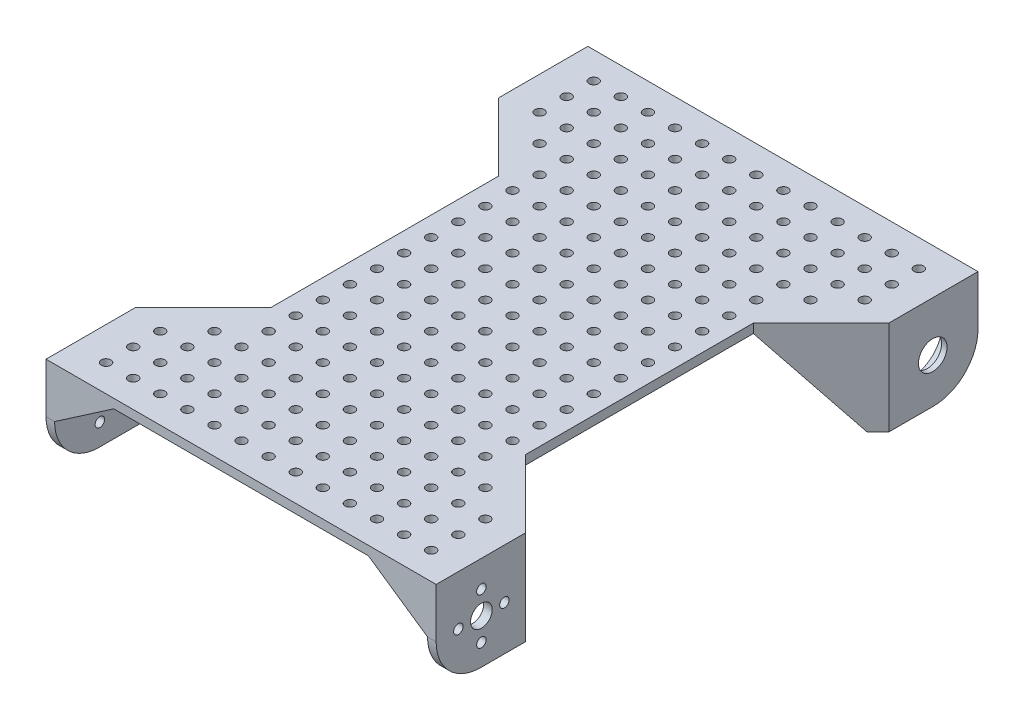
SolidWorks part; units mm, degrees
ref_plane "Alzado" through (0, 0, 0) normal (0, 0, 1) x (1, 0, 0)
ref_plane "Planta" through (0, 0, 0) normal (0, 1, 0) x (1, 0, 0)
ref_plane "Vista lateral" through (0, 0, 0) normal (1, 0, 0) x (0, 0, -1)
sketch "Croquis1" plane through (0, 0, 0) normal (1, 0, 0) x (0, 0, -1)
  point P0 (0, 0)
  line B0 (-67.1, 0) -> (67.1, 0)
  line B1 (-100, 0) -> (-100, 3.3682)
  line B2 (-100, 3.3682) -> (100, 3.3682)
  line B3 (-100, 0) -> (-100, -15)
  line B4 (-67.1, -15) -> (-70.1, -15) construction
  line B5 (-100, 0) -> (-67.1, 0) construction
  line B6 (-67.1, -15) -> (-67.1, 0)
  line B7 (0, 3.3682) -> (0, 0) construction
  line B8 (100, 0) -> (67.1, 0) construction
  line B9 (100, 0) -> (100, 3.3682)
  line B10 (100, 0) -> (67.1, 0) construction
  line B11 (100, 0) -> (100, -15)
  line B12 (67.1, -15) -> (67.1, 0)
  arc B13 (-100, -15) -> (-67.1, -15) centre (-83.55, -15) ccw
  circle B14 centre (-83.3, -15) radius 13.2 construction
  circle B15 centre (-83.3, -23.5) radius 1.75
  circle B16 centre (-91.8, -15) radius 1.75
  circle B17 centre (-74.8, -15) radius 1.75
  circle B18 centre (-83.3, -6.5) radius 1.75
  circle B19 centre (-83.3, -15) radius 4
  circle B20 centre (83.3, -15) radius 5.275
  arc B21 (100, -15) -> (67.1, -15) centre (83.55, -15) cw
sketch_block_instance "Bloque1-1"
sketch_block "Bloque1"
extrude "Saliente-Extruir1" add sketch "Croquis1" along normal blind 2
sketch "Croquis2" plane through (2, 0, 0) normal (1, 0, 0) x (0, 0, -1)
  line L0 (100, -15) -> (100, 3.3682) construction
  line L1 (-100, 3.3682) -> (100, 3.3682)
  line L2 (-100, 3.3682) -> (-100, 0)
  line L3 (-100, 0) -> (100, 0)
  line L4 (100, 3.3682) -> (100, 0)
extrude "Saliente-Extruir2" add sketch "Croquis2" along normal blind 70
sketch "Croquis3" plane through (0, 0, 0) normal (0, -1, 0) x (1, 0, 0)
  line L0 (0, 67.1) -> (25, 42.1)
  line L1 (25, 42.1) -> (25, -42.1)
  line L2 (25, -42.1) -> (0, -67.1)
  line L3 (0, -67.1) -> (0, 67.1)
  dimension "D1" = 25
  dimension "D2" = 25
  dimension "D3" = 25
extrude "Cortar-Extruir1" cut sketch "Croquis3" against normal through all
sketch "Croquis5" plane through (2, 0, 0) normal (1, 0, 0) x (0, 0, -1)
  line L3 (-67.1, 0) -> (-100, 0)
  line L4 (-100, 0) -> (-100, -15)
  line L5 (-67.1, -15) -> (-67.1, 0)
  line L6 (-67.1, 0) -> (-100, 0)
  line L7 (-100, 0) -> (-100, -15)
  line L8 (-67.1, -15) -> (-67.1, 0)
  circle A1 centre (-83.3, -23.5) radius 1.75
  circle A2 centre (-83.3, -23.5) radius 1.75
  circle A3 centre (-91.8, -15) radius 1.75
  circle A4 centre (-91.8, -15) radius 1.75
  circle A5 centre (-74.8, -15) radius 1.75
  circle A6 centre (-74.8, -15) radius 1.75
  circle A7 centre (-83.3, -6.5) radius 1.75
  circle A8 centre (-83.3, -6.5) radius 1.75
  circle A9 centre (-83.3, -15) radius 4
  circle A10 centre (-83.3, -15) radius 4
  arc A11 (-100, -15) -> (-67.1, -15) centre (-83.55, -15) ccw
  arc A12 (-100, -15) -> (-67.1, -15) centre (-83.55, -15) ccw
  dimension "D1" = 0
  dimension "D2" = 0
  dimension "D3" = 0
  dimension "D4" = 0
  dimension "D5" = 0
  dimension "D6" = 0
extrude "Saliente-Extruir3" add sketch "Croquis5" along normal blind 1.175
sketch "Croquis6" plane through (2, 0, 0) normal (1, 0, 0) x (0, 0, -1)
  line L3 (100, 0) -> (67.1, 0)
  line L4 (67.1, 0) -> (67.1, -15)
  line L5 (100, -15) -> (100, 0)
  line L6 (100, 0) -> (67.1, 0)
  line L7 (67.1, 0) -> (67.1, -15)
  line L8 (100, -15) -> (100, 0)
  circle A0 centre (83.55, -15) radius 11.25
  arc A1 (67.1, -15) -> (100, -15) centre (83.55, -15) ccw
  arc A2 (67.1, -15) -> (100, -15) centre (83.55, -15) ccw
  dimension "D2" = 22.5
  dimension "D1" = 0
extrude "Saliente-Extruir4" add sketch "Croquis6" along normal blind 6.05
sketch "Croquis8" plane through (3.175, 0, 0) normal (1, 0, 0) x (0, 0, -1)
  line L0 (-83.55, -31.45) -> (-67.1, -31.45)
  line L1 (-67.1, -31.45) -> (-67.1, -15)
  line L2 (83.55, -31.45) -> (67.1, -31.45)
  line L3 (-67.1, -15) -> (-67.1, 0)
  line L4 (-67.1, 0) -> (-100, 0)
  line L5 (-100, 0) -> (-100, -15)
  line L9 (67.1, -31.45) -> (67.1, -15)
  arc A0 (67.1, -15) -> (100, -15) centre (83.55, -15) ccw construction
  arc A1 (-100, -15) -> (-67.1, -15) centre (-83.55, -15) ccw
  arc A2 (-83.55, -31.45) -> (-67.1, -15) centre (-83.55, -15) ccw
  arc A3 (67.1, -15) -> (83.55, -31.45) centre (83.55, -15) ccw
  dimension "D1" = 0
extrude "Saliente-Extruir5" add sketch "Croquis8" against normal up to surface (3.175 mm away) up to face at (0, -15, 79.3)
sketch "Croquis10" plane through (3.175, 0, 0) normal (1, 0, 0) x (0, 0, -1)
  line L2 (67.1, -15) -> (67.1, -31.45)
  line L3 (67.1, -31.45) -> (83.55, -31.45)
  line L4 (67.1, -15) -> (67.1, -31.45)
  line L5 (67.1, -31.45) -> (83.55, -31.45)
  arc A1 (67.1, -15) -> (83.55, -31.45) centre (83.55, -15) ccw
  arc A2 (67.1, -15) -> (83.55, -31.45) centre (83.55, -15) ccw
  dimension "D1" = 0
extrude "Saliente-Extruir6" add sketch "Croquis10" along normal up to surface (4.875 mm away) up to face at (8.05, -11.6125, -83.55)
sketch "Croquis9" plane through (0, 0, 0) normal (0, -1, 0) x (1, 0, 0)
  line L0 (0, 67.1) -> (25, 42.1)
  line L1 (25, 42.1) -> (25, 45.275)
  line L2 (25, 45.275) -> (3.175, 67.1)
  line L3 (0, -67.1) -> (25, -42.1)
  line L4 (25, -42.1) -> (25, -50.15)
  line L5 (25, -50.15) -> (8.05, -67.1)
  line L6 (8.05, -100) -> (8.05, -67.1) construction
  line L7 (8.05, -67.1) -> (0, -67.1)
  line M3 (0, -67.1) -> (8.05, -67.1)
  line M9 (3.175, 67.1) -> (0, 67.1)
  line M10 (0, 67.1) -> (25, 42.1)
  line M12 (25, -42.1) -> (0, -67.1)
extrude "Saliente-Extruir7" add sketch "Croquis9" along normal up to surface (31.45 mm away) contours L1 L2 M9 M10 | L5 L4 M12 M3 up to face at (1.5875, -31.45, 75.325)
sketch "Croquis11" plane through (37.575, 0, -37.575) normal (0.7071, 0, -0.7071) x (-0.7071, 0, -0.7071)
  line L0 (41.7547, -31.45) -> (12.0915, 0)
  line L1 (12.0915, 0) -> (12.0915, -31.45)
  line L2 (12.0915, -31.45) -> (41.7547, -31.45)
extrude "Cortar-Extruir2" cut sketch "Croquis11" against normal through all
sketch "Croquis12" plane through (35.1375, 0, 35.1375) normal (0.7071, 0, 0.7071) x (0.7071, 0, -0.7071)
  line L0 (-45.2018, -31.45) -> (-12.0915, 0)
  line L1 (-12.0915, 0) -> (-12.0915, -31.45)
  line L2 (-12.0915, -31.45) -> (-45.2018, -31.45)
extrude "Cortar-Extruir3" cut sketch "Croquis12" against normal through all
sketch "Croquis13" plane through (3.175, 0, 0) normal (1, 0, 0) x (0, 0, -1)
  line L0 (-100, 0) -> (-100, -15) construction
  line L1 (-100, 0) -> (-97, 0)
  line L2 (-100, 0) -> (-100, -15)
  line L3 (-100, -15) -> (-97, -15)
  line L4 (-97, 0) -> (-97, -15)
  line L5 (100, 0) -> (97, 0)
  line L6 (100, 0) -> (100, -15)
  line L7 (100, -15) -> (97, -15)
  line L8 (97, 0) -> (97, -15)
  line L9 (100, -15) -> (100, 0) construction
  point P10 (-100, -11.6728)
  point P14 (100, -13.4156)
  dimension "D1" = 3
  dimension "D2" = 3
extrude "Saliente-Extruir8" add sketch "Croquis13" along normal up to surface (21.825 mm away) up to face at (25, 1.6841, 0)
sketch "Croquis14" plane through (0, 0, 100) normal (0, 0, 1) x (1, 0, 0)
  line L0 (3.175, -15) -> (25, 0)
  line L1 (25, 0) -> (25, -15)
  line L2 (25, -15) -> (3.175, -15)
extrude "Cortar-Extruir4" cut sketch "Croquis14" against normal up to surface (3 mm away) up to face at (14.0875, -7.5, 97)
sketch "Croquis15" plane through (0, 0, -100) normal (0, 0, -1) x (-1, 0, 0)
  line L0 (-8.05, -15) -> (-25, 0)
  line L1 (-25, 0) -> (-25, -15)
  line L2 (-25, -15) -> (-8.05, -15)
extrude "Cortar-Extruir5" cut sketch "Croquis15" against normal up to surface (3 mm away) up to face at (16.525, -7.5, -97)
ref_plane "Plano1" through (72, 0, 0) normal (1, 0, 0) x (0, 0, -1)
mirror "Simetría1" about plane through (72, 0, 0) normal (1, 0, 0) of bodies 113
sketch "Croquis16" plane through (0, 0, 0) normal (0, -1, 0) x (1, 0, 0)
  line L0 (3.175, 97) -> (3.175, -97) construction
  line L1 (25, -97) -> (8.05, -97) construction
  line L2 (119, 100) -> (25, 100) construction
  line L3 (72, 100) -> (72, -100) construction
  line L4 (119, 100) -> (25, 100) construction
  line L5 (119, -100) -> (25, -100) construction
  circle A0 centre (12.175, 90) radius 1.75
  circle A1 centre (22.175, 90) radius 1.75
  circle A2 centre (32.175, 90) radius 1.75
  circle A3 centre (42.175, 90) radius 1.75
  circle A4 centre (52.175, 90) radius 1.75
  circle A5 centre (62.175, 90) radius 1.75
  circle A6 centre (72.175, 90) radius 1.75
  circle A7 centre (82.175, 90) radius 1.75
  circle A8 centre (92.175, 90) radius 1.75
  circle A9 centre (102.175, 90) radius 1.75
  circle A10 centre (112.175, 90) radius 1.75
  circle A11 centre (122.175, 90) radius 1.75
  circle A12 centre (132.175, 90) radius 1.75
  circle A13 centre (22.175, 80) radius 1.75
  circle A14 centre (32.175, 80) radius 1.75
  circle A15 centre (42.175, 80) radius 1.75
  circle A16 centre (52.175, 80) radius 1.75
  circle A17 centre (62.175, 80) radius 1.75
  circle A18 centre (72.175, 80) radius 1.75
  circle A19 centre (82.175, 80) radius 1.75
  circle A20 centre (92.175, 80) radius 1.75
  circle A21 centre (102.175, 80) radius 1.75
  circle A22 centre (112.175, 80) radius 1.75
  circle A23 centre (122.175, 80) radius 1.75
  circle A24 centre (132.175, 80) radius 1.75
  circle A25 centre (22.175, 70) radius 1.75
  circle A26 centre (32.175, 70) radius 1.75
  circle A27 centre (42.175, 70) radius 1.75
  circle A28 centre (52.175, 70) radius 1.75
  circle A29 centre (62.175, 70) radius 1.75
  circle A30 centre (72.175, 70) radius 1.75
  circle A31 centre (82.175, 70) radius 1.75
  circle A32 centre (92.175, 70) radius 1.75
  circle A33 centre (102.175, 70) radius 1.75
  circle A34 centre (112.175, 70) radius 1.75
  circle A35 centre (122.175, 70) radius 1.75
  circle A36 centre (132.175, 70) radius 1.75
  circle A37 centre (22.175, 60) radius 1.75
  circle A38 centre (32.175, 60) radius 1.75
  circle A39 centre (42.175, 60) radius 1.75
  circle A40 centre (52.175, 60) radius 1.75
  circle A41 centre (62.175, 60) radius 1.75
  circle A42 centre (72.175, 60) radius 1.75
  circle A43 centre (82.175, 60) radius 1.75
  circle A44 centre (92.175, 60) radius 1.75
  circle A45 centre (102.175, 60) radius 1.75
  circle A46 centre (112.175, 60) radius 1.75
  circle A47 centre (122.175, 60) radius 1.75
  circle A50 centre (32.175, 50) radius 1.75
  circle A51 centre (42.175, 50) radius 1.75
  circle A52 centre (52.175, 50) radius 1.75
  circle A53 centre (62.175, 50) radius 1.75
  circle A54 centre (72.175, 50) radius 1.75
  circle A55 centre (82.175, 50) radius 1.75
  circle A56 centre (92.175, 50) radius 1.75
  circle A57 centre (102.175, 50) radius 1.75
  circle A58 centre (112.175, 50) radius 1.75
  circle A62 centre (32.175, 40) radius 1.75
  circle A63 centre (42.175, 40) radius 1.75
  circle A64 centre (52.175, 40) radius 1.75
  circle A65 centre (62.175, 40) radius 1.75
  circle A66 centre (72.175, 40) radius 1.75
  circle A67 centre (82.175, 40) radius 1.75
  circle A68 centre (92.175, 40) radius 1.75
  circle A69 centre (102.175, 40) radius 1.75
  circle A70 centre (112.175, 40) radius 1.75
  circle A74 centre (32.175, 30) radius 1.75
  circle A75 centre (42.175, 30) radius 1.75
  circle A76 centre (52.175, 30) radius 1.75
  circle A77 centre (62.175, 30) radius 1.75
  circle A78 centre (72.175, 30) radius 1.75
  circle A79 centre (82.175, 30) radius 1.75
  circle A80 centre (92.175, 30) radius 1.75
  circle A81 centre (102.175, 30) radius 1.75
  circle A82 centre (112.175, 30) radius 1.75
  circle A86 centre (32.175, 20) radius 1.75
  circle A87 centre (42.175, 20) radius 1.75
  circle A88 centre (52.175, 20) radius 1.75
  circle A89 centre (62.175, 20) radius 1.75
  circle A90 centre (72.175, 20) radius 1.75
  circle A91 centre (82.175, 20) radius 1.75
  circle A92 centre (92.175, 20) radius 1.75
  circle A93 centre (102.175, 20) radius 1.75
  circle A94 centre (112.175, 20) radius 1.75
  circle A98 centre (32.175, 10) radius 1.75
  circle A99 centre (42.175, 10) radius 1.75
  circle A100 centre (52.175, 10) radius 1.75
  circle A101 centre (62.175, 10) radius 1.75
  circle A102 centre (72.175, 10) radius 1.75
  circle A103 centre (82.175, 10) radius 1.75
  circle A104 centre (92.175, 10) radius 1.75
  circle A105 centre (102.175, 10) radius 1.75
  circle A106 centre (112.175, 10) radius 1.75
  circle A110 centre (32.175, 0) radius 1.75
  circle A111 centre (42.175, 0) radius 1.75
  circle A112 centre (52.175, 0) radius 1.75
  circle A113 centre (62.175, 0) radius 1.75
  circle A114 centre (72.175, 0) radius 1.75
  circle A115 centre (82.175, 0) radius 1.75
  circle A116 centre (92.175, 0) radius 1.75
  circle A117 centre (102.175, 0) radius 1.75
  circle A118 centre (112.175, 0) radius 1.75
  circle A122 centre (32.175, -10) radius 1.75
  circle A123 centre (42.175, -10) radius 1.75
  circle A124 centre (52.175, -10) radius 1.75
  circle A125 centre (62.175, -10) radius 1.75
  circle A126 centre (72.175, -10) radius 1.75
  circle A127 centre (82.175, -10) radius 1.75
  circle A128 centre (92.175, -10) radius 1.75
  circle A129 centre (102.175, -10) radius 1.75
  circle A130 centre (112.175, -10) radius 1.75
  circle A134 centre (32.175, -20) radius 1.75
  circle A135 centre (42.175, -20) radius 1.75
  circle A136 centre (52.175, -20) radius 1.75
  circle A137 centre (62.175, -20) radius 1.75
  circle A138 centre (72.175, -20) radius 1.75
  circle A139 centre (82.175, -20) radius 1.75
  circle A140 centre (92.175, -20) radius 1.75
  circle A141 centre (102.175, -20) radius 1.75
  circle A142 centre (112.175, -20) radius 1.75
  circle A146 centre (32.175, -30) radius 1.75
  circle A147 centre (42.175, -30) radius 1.75
  circle A148 centre (52.175, -30) radius 1.75
  circle A149 centre (62.175, -30) radius 1.75
  circle A150 centre (72.175, -30) radius 1.75
  circle A151 centre (82.175, -30) radius 1.75
  circle A152 centre (92.175, -30) radius 1.75
  circle A153 centre (102.175, -30) radius 1.75
  circle A154 centre (112.175, -30) radius 1.75
  circle A158 centre (32.175, -40) radius 1.75
  circle A159 centre (42.175, -40) radius 1.75
  circle A160 centre (52.175, -40) radius 1.75
  circle A161 centre (62.175, -40) radius 1.75
  circle A162 centre (72.175, -40) radius 1.75
  circle A163 centre (82.175, -40) radius 1.75
  circle A164 centre (92.175, -40) radius 1.75
  circle A165 centre (102.175, -40) radius 1.75
  circle A166 centre (112.175, -40) radius 1.75
  circle A170 centre (32.175, -50) radius 1.75
  circle A171 centre (42.175, -50) radius 1.75
  circle A172 centre (52.175, -50) radius 1.75
  circle A173 centre (62.175, -50) radius 1.75
  circle A174 centre (72.175, -50) radius 1.75
  circle A175 centre (82.175, -50) radius 1.75
  circle A176 centre (92.175, -50) radius 1.75
  circle A177 centre (102.175, -50) radius 1.75
  circle A178 centre (112.175, -50) radius 1.75
  circle A181 centre (22.175, -60) radius 1.75
  circle A182 centre (32.175, -60) radius 1.75
  circle A183 centre (42.175, -60) radius 1.75
  circle A184 centre (52.175, -60) radius 1.75
  circle A185 centre (62.175, -60) radius 1.75
  circle A186 centre (72.175, -60) radius 1.75
  circle A187 centre (82.175, -60) radius 1.75
  circle A188 centre (92.175, -60) radius 1.75
  circle A189 centre (102.175, -60) radius 1.75
  circle A190 centre (112.175, -60) radius 1.75
  circle A191 centre (122.175, -60) radius 1.75
  circle A193 centre (22.175, -70) radius 1.75
  circle A194 centre (32.175, -70) radius 1.75
  circle A195 centre (42.175, -70) radius 1.75
  circle A196 centre (52.175, -70) radius 1.75
  circle A197 centre (62.175, -70) radius 1.75
  circle A198 centre (72.175, -70) radius 1.75
  circle A199 centre (82.175, -70) radius 1.75
  circle A200 centre (92.175, -70) radius 1.75
  circle A201 centre (102.175, -70) radius 1.75
  circle A202 centre (112.175, -70) radius 1.75
  circle A203 centre (122.175, -70) radius 1.75
  circle A204 centre (132.175, -70) radius 1.75
  circle A205 centre (22.175, -80) radius 1.75
  circle A206 centre (32.175, -80) radius 1.75
  circle A207 centre (42.175, -80) radius 1.75
  circle A208 centre (52.175, -80) radius 1.75
  circle A209 centre (62.175, -80) radius 1.75
  circle A210 centre (72.175, -80) radius 1.75
  circle A211 centre (82.175, -80) radius 1.75
  circle A212 centre (92.175, -80) radius 1.75
  circle A213 centre (102.175, -80) radius 1.75
  circle A214 centre (112.175, -80) radius 1.75
  circle A215 centre (122.175, -80) radius 1.75
  circle A216 centre (132.175, -80) radius 1.75
  circle A217 centre (22.175, -90) radius 1.75
  circle A218 centre (32.175, -90) radius 1.75
  circle A219 centre (42.175, -90) radius 1.75
  circle A220 centre (52.175, -90) radius 1.75
  circle A221 centre (62.175, -90) radius 1.75
  circle A222 centre (72.175, -90) radius 1.75
  circle A223 centre (82.175, -90) radius 1.75
  circle A224 centre (92.175, -90) radius 1.75
  circle A225 centre (102.175, -90) radius 1.75
  circle A226 centre (112.175, -90) radius 1.75
  circle A227 centre (122.175, -90) radius 1.75
  circle A228 centre (132.175, -90) radius 1.75
  circle A229 centre (12.175, 80) radius 1.75
  circle A230 centre (12.175, 70) radius 1.75
  circle A244 centre (12.175, -70) radius 1.75
  circle A245 centre (12.175, -80) radius 1.75
  circle A246 centre (12.175, -90) radius 1.75
  circle A247 centre (22.175, 40) radius 1.75 [skipped]
  circle A248 centre (12.175, 60) radius 1.75 [skipped]
  circle A249 centre (22.175, 50) radius 1.75 [skipped]
  circle A250 centre (22.175, 30) radius 1.75 [skipped]
  circle A251 centre (22.175, 20) radius 1.75 [skipped]
  circle A252 centre (22.175, 10) radius 1.75 [skipped]
  circle A253 centre (22.175, 0) radius 1.75 [skipped]
  circle A254 centre (22.175, -10) radius 1.75 [skipped]
  circle A255 centre (22.175, -20) radius 1.75 [skipped]
  circle A256 centre (22.175, -30) radius 1.75 [skipped]
  circle A257 centre (22.175, -40) radius 1.75 [skipped]
  circle A258 centre (22.175, -50) radius 1.75 [skipped]
  circle A259 centre (12.175, 50) radius 1.75 [skipped]
  circle A260 centre (12.175, 40) radius 1.75 [skipped]
  circle A261 centre (12.175, 30) radius 1.75 [skipped]
  circle A262 centre (12.175, 20) radius 1.75 [skipped]
  circle A263 centre (12.175, 10) radius 1.75 [skipped]
  circle A264 centre (12.175, 0) radius 1.75 [skipped]
  circle A265 centre (12.175, -10) radius 1.75 [skipped]
  circle A266 centre (12.175, -20) radius 1.75 [skipped]
  circle A267 centre (12.175, -30) radius 1.75 [skipped]
  circle A268 centre (12.175, -40) radius 1.75 [skipped]
  circle A269 centre (12.175, -50) radius 1.75 [skipped]
  circle A270 centre (12.175, -60) radius 1.75 [skipped]
  circle A271 centre (122.175, 50) radius 1.75 [skipped]
  circle A272 centre (132.175, 50) radius 1.75 [skipped]
  circle A273 centre (122.175, 40) radius 1.75 [skipped]
  circle A274 centre (132.175, 40) radius 1.75 [skipped]
  circle A275 centre (122.175, 30) radius 1.75 [skipped]
  circle A276 centre (132.175, 30) radius 1.75 [skipped]
  circle A277 centre (122.175, 20) radius 1.75 [skipped]
  circle A278 centre (132.175, 20) radius 1.75 [skipped]
  circle A279 centre (122.175, 10) radius 1.75 [skipped]
  circle A280 centre (132.175, 10) radius 1.75 [skipped]
  circle A281 centre (122.175, 0) radius 1.75 [skipped]
  circle A282 centre (132.175, 0) radius 1.75 [skipped]
  circle A283 centre (122.175, -10) radius 1.75 [skipped]
  circle A284 centre (132.175, -10) radius 1.75 [skipped]
  circle A285 centre (122.175, -20) radius 1.75 [skipped]
  circle A286 centre (132.175, -20) radius 1.75 [skipped]
  circle A287 centre (122.175, -30) radius 1.75 [skipped]
  circle A288 centre (132.175, -30) radius 1.75 [skipped]
  circle A289 centre (122.175, -40) radius 1.75 [skipped]
  circle A290 centre (132.175, -40) radius 1.75 [skipped]
  circle A291 centre (122.175, -50) radius 1.75 [skipped]
  circle A292 centre (132.175, -50) radius 1.75 [skipped]
  circle A293 centre (132.175, 60) radius 1.75 [skipped]
  circle A294 centre (132.175, -60) radius 1.75 [skipped]
  dimension "D1" = 3.5
  dimension "D2" = 9
  dimension "D3" = 10
  dimension "D6" = 10
  dimension "D7" = 10
  dimension "D4" = 13
  dimension "D5" = 19
extrude "Cortar-Extruir6" cut sketch "Croquis16" against normal through all
